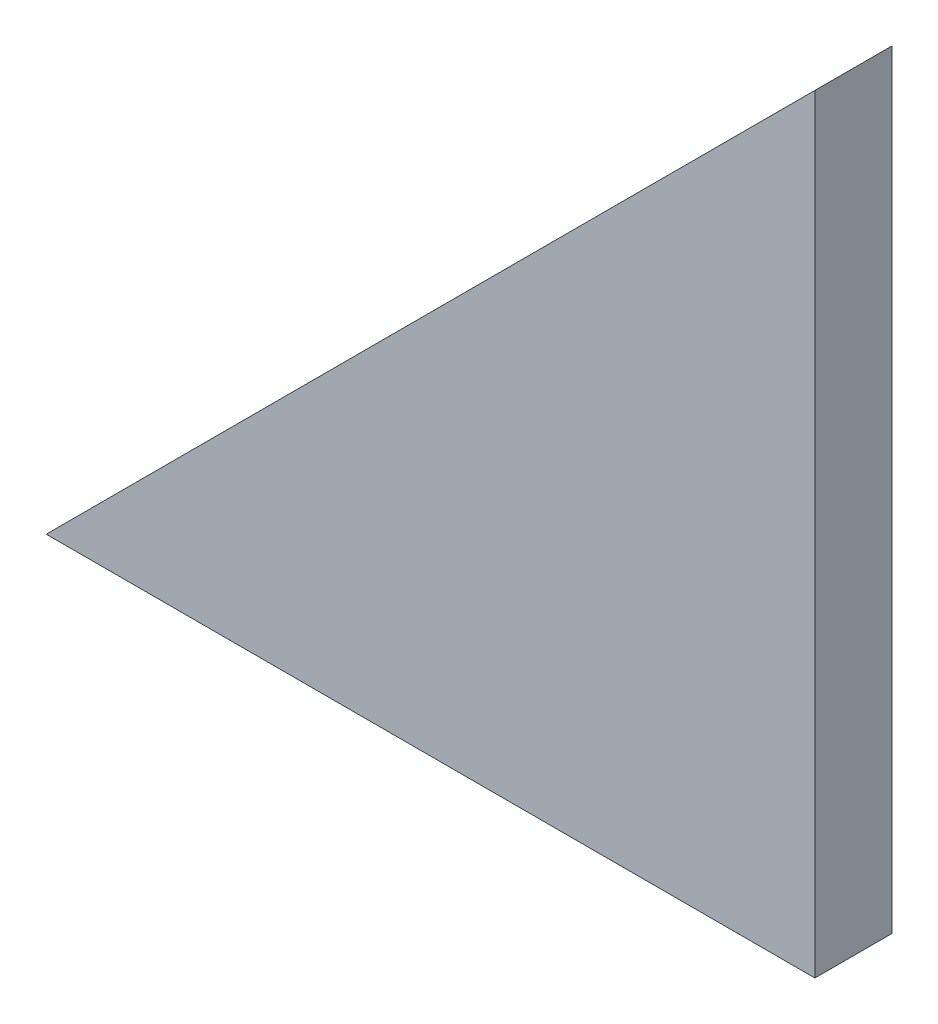
SolidWorks part; units mm, degrees
ref_plane "前视基准面" through (0, 0, 0) normal (0, 0, 1) x (1, 0, 0)
ref_plane "上视基准面" through (0, 0, 0) normal (0, 1, 0) x (1, 0, 0)
ref_plane "右视基准面" through (0, 0, 0) normal (1, 0, 0) x (0, 0, -1)
sketch "草图1" plane through (0, 0, 0) normal (0, 0, 1) x (1, 0, 0)
  line L0 (-76.2938, -37.9185) -> (-26.2938, -37.9185)
  line L1 (-26.2938, -37.9185) -> (-26.2938, 12.0815)
  line L2 (-26.2938, 12.0815) -> (-76.2938, -37.9185)
extrude "凸台-拉伸1" add sketch "草图1" along normal blind 5
